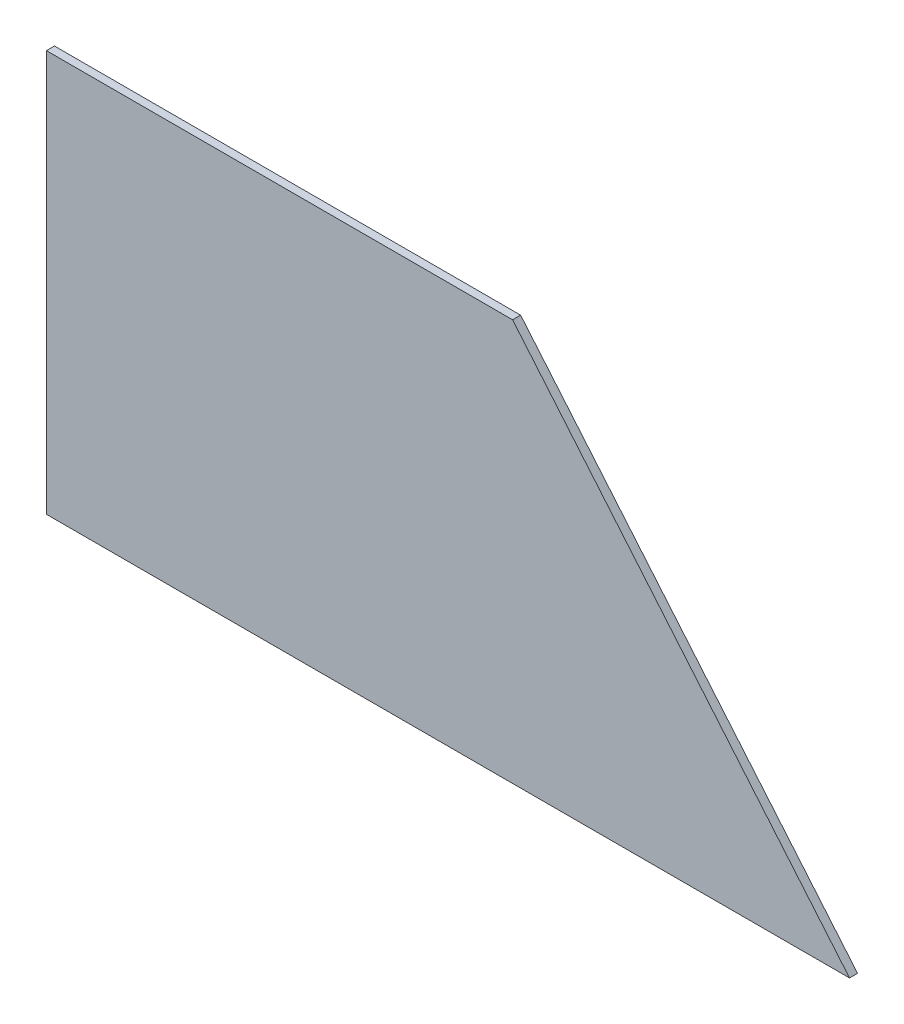
SolidWorks part; units mm, degrees
ref_plane "Front Plane" through (0, 0, 0) normal (0, 0, 1) x (1, 0, 0)
ref_plane "Top Plane" through (0, 0, 0) normal (0, 1, 0) x (1, 0, 0)
ref_plane "Right Plane" through (0, 0, 0) normal (1, 0, 0) x (0, 0, -1)
sketch "ｽｹｯﾁ1" plane through (0, 0, 0) normal (0, 0, 1) x (1, 0, 0)
  line L0 (0, 0) -> (200, 0)
  line L1 (200, 0) -> (116.09, 100)
  line L2 (116.09, 100) -> (0, 100)
  line L3 (0, 100) -> (0, 0)
  dimension "D1" = 50
  dimension "D2" = 200
  dimension "D3" = 100
extrude "ﾎﾞｽ - 押し出し1" add sketch "ｽｹｯﾁ1" along normal blind 2 contours L2 L3 L0 L1
